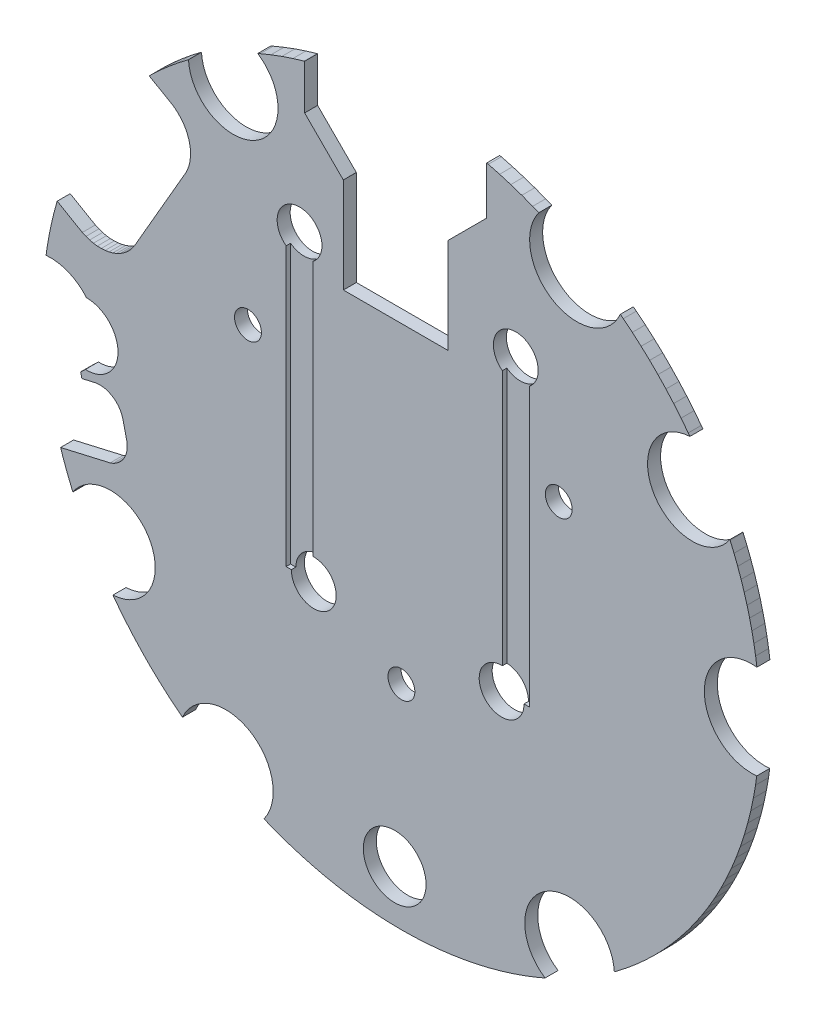
SolidWorks part; units mm, degrees
ref_plane "Płaszczyzna przednia" through (0, 0, 0) normal (0, 0, 1) x (1, 0, 0)
ref_plane "Płaszczyzna górna" through (0, 0, 0) normal (0, 1, 0) x (1, 0, 0)
ref_plane "Płaszczyzna prawa" through (0, 0, 0) normal (1, 0, 0) x (0, 0, -1)
sketch "Szkic1" plane through (0, 0, 0) normal (0, 0, 1) x (1, 0, 0)
  line L362 (-71.5796, -7.9834) -> (-71.3126, -9.14)
  line L363 (-71.3126, -9.14) -> (-68.5352, -8.4988)
  line L364 (-68.5352, -8.4988) -> (-68.1939, -8.42)
  line L365 (-68.1939, -8.42) -> (-67.4966, -8.3528)
  line L366 (-67.4966, -8.3528) -> (-66.7965, -8.3773)
  line L367 (-66.7965, -8.3773) -> (-66.1056, -8.4929)
  line L368 (-66.1056, -8.4929) -> (-65.4357, -8.6977)
  line L369 (-65.4357, -8.6977) -> (-64.7982, -8.9882)
  line L370 (-64.7982, -8.9882) -> (-64.2042, -9.3594)
  line L371 (-64.2042, -9.3594) -> (-63.6636, -9.805)
  line L372 (-63.6636, -9.805) -> (-63.1859, -10.3174)
  line L373 (-63.1859, -10.3174) -> (-62.7791, -10.8877)
  line L374 (-62.7791, -10.8877) -> (-62.4502, -11.5062)
  line L375 (-62.4502, -11.5062) -> (-62.2049, -12.1624)
  line L376 (-62.2049, -12.1624) -> (-62.1261, -12.5037)
  line L377 (-62.1261, -12.5037) -> (-61.3306, -15.949)
  line L378 (-61.3306, -15.949) -> (-61.2518, -16.2903)
  line L379 (-61.2518, -16.2903) -> (-61.1847, -16.9876)
  line L380 (-61.1847, -16.9876) -> (-61.2092, -17.6877)
  line L381 (-61.2092, -17.6877) -> (-61.3248, -18.3787)
  line L382 (-61.3248, -18.3787) -> (-61.5296, -19.0486)
  line L383 (-61.5296, -19.0486) -> (-61.8201, -19.686)
  line L384 (-61.8201, -19.686) -> (-62.1913, -20.2801)
  line L385 (-62.1913, -20.2801) -> (-62.6369, -20.8206)
  line L386 (-62.6369, -20.8206) -> (-63.1492, -21.2984)
  line L387 (-63.1492, -21.2984) -> (-63.7196, -21.7052)
  line L388 (-63.7196, -21.7052) -> (-64.3381, -22.0341)
  line L389 (-64.3381, -22.0341) -> (-64.9942, -22.2794)
  line L390 (-64.9942, -22.2794) -> (-65.3355, -22.3582)
  line L391 (-65.3355, -22.3582) -> (-76.0559, -24.8332)
  line L392 (-76.0559, -24.8332) -> (-75.5463, -26.3728)
  line L393 (-75.5463, -26.3728) -> (-74.6507, -28.8104)
  line L394 (-74.6507, -28.8104) -> (-73.6765, -31.2177)
  line L395 (-73.6765, -31.2177) -> (-73.3045, -32.0573)
  line L396 (-64.3703, -47.5137) -> (-63.5862, -48.5784)
  line L397 (-63.5862, -48.5784) -> (-61.8317, -50.7929)
  line L398 (-61.8317, -50.7929) -> (-60, -52.944)
  line L399 (-60, -52.944) -> (-58.0936, -55.0292)
  line L400 (-58.0936, -55.0292) -> (-56.1147, -57.0457)
  line L401 (-56.1147, -57.0457) -> (-54.0659, -58.9911)
  line L402 (-54.0659, -58.9911) -> (-51.9496, -60.863)
  line L403 (-51.9496, -60.863) -> (-49.7687, -62.659)
  line L404 (-49.7687, -62.659) -> (-48.854, -63.3595)
  line L405 (-30.6643, -73.9045) -> (-30.3309, -74.048)
  line L406 (-30.3309, -74.048) -> (-27.6979, -75.0726)
  line L407 (-27.6979, -75.0726) -> (-25.0304, -76.0036)
  line L408 (-25.0304, -76.0036) -> (-22.3317, -76.8399)
  line L409 (-22.3317, -76.8399) -> (-19.6051, -77.5804)
  line L410 (-19.6051, -77.5804) -> (-16.8541, -78.2241)
  line L411 (-16.8541, -78.2241) -> (-14.0821, -78.7703)
  line L412 (-14.0821, -78.7703) -> (-11.2926, -79.2184)
  line L413 (-11.2926, -79.2184) -> (-8.4889, -79.5676)
  line L414 (-8.4889, -79.5676) -> (-5.6747, -79.8177)
  line L415 (-5.6747, -79.8177) -> (-2.8534, -79.9683)
  line L416 (-2.8534, -79.9683) -> (-0.0286, -80.0192)
  line L417 (-0.0286, -80.0192) -> (2.7963, -79.9703)
  line L418 (2.7963, -79.9703) -> (5.6177, -79.8218)
  line L419 (5.6177, -79.8218) -> (8.4321, -79.5737)
  line L420 (8.4321, -79.5737) -> (11.236, -79.2264)
  line L421 (11.236, -79.2264) -> (14.0259, -78.7804)
  line L422 (14.0259, -78.7804) -> (16.7983, -78.2361)
  line L423 (16.7983, -78.2361) -> (19.5497, -77.5943)
  line L424 (19.5497, -77.5943) -> (22.2768, -76.8558)
  line L425 (22.2768, -76.8558) -> (24.9761, -76.0215)
  line L426 (24.9761, -76.0215) -> (27.6443, -75.0924)
  line L427 (27.6443, -75.0924) -> (30.278, -74.0697)
  line L428 (30.278, -74.0697) -> (32.0581, -73.3051)
  line L429 (47.514, -64.3751) -> (47.9923, -64.0295)
  line L430 (47.9923, -64.0295) -> (50.2037, -62.3107)
  line L431 (50.2037, -62.3107) -> (52.3536, -60.5156)
  line L432 (52.3536, -60.5156) -> (54.4394, -58.6463)
  line L433 (54.4394, -58.6463) -> (56.4584, -56.7052)
  line L434 (56.4584, -56.7052) -> (58.4083, -54.6947)
  line L435 (58.4083, -54.6947) -> (60.2867, -52.6171)
  line L436 (60.2867, -52.6171) -> (62.0911, -50.475)
  line L437 (62.0911, -50.475) -> (63.8195, -48.2711)
  line L438 (63.8195, -48.2711) -> (65.4698, -46.0081)
  line L439 (65.4698, -46.0081) -> (67.0398, -43.6887)
  line L440 (67.0398, -43.6887) -> (68.5277, -41.3158)
  line L441 (68.5277, -41.3158) -> (69.9316, -38.8923)
  line L442 (69.9316, -38.8923) -> (71.2498, -36.4211)
  line L443 (71.2498, -36.4211) -> (72.4808, -33.9053)
  line L444 (72.4808, -33.9053) -> (73.623, -31.348)
  line L445 (73.623, -31.348) -> (74.6749, -28.7523)
  line L446 (74.6749, -28.7523) -> (75.6354, -26.1213)
  line L447 (75.6354, -26.1213) -> (76.5032, -23.4583)
  line L448 (76.5032, -23.4583) -> (77.2773, -20.7666)
  line L449 (77.2773, -20.7666) -> (77.9567, -18.0495)
  line L450 (77.9567, -18.0495) -> (78.5407, -15.3102)
  line L451 (78.5407, -15.3102) -> (79.0284, -12.5522)
  line L452 (79.0284, -12.5522) -> (79.2994, -10.6289)
  line L453 (79.3336, 10.3964) -> (79.0449, 12.4201)
  line L454 (79.0449, 12.4201) -> (78.6613, 14.6547)
  line L455 (78.6613, 14.6547) -> (78.2145, 16.8775)
  line L456 (78.2145, 16.8775) -> (77.7049, 19.0868)
  line L457 (77.7049, 19.0868) -> (77.1329, 21.2808)
  line L458 (77.1329, 21.2808) -> (76.499, 23.4576)
  line L459 (76.499, 23.4576) -> (75.8037, 25.6157)
  line L460 (75.8037, 25.6157) -> (75.0475, 27.7531)
  line L461 (75.0475, 27.7531) -> (74.231, 29.8683)
  line L462 (74.231, 29.8683) -> (73.355, 31.9595)
  line L463 (73.355, 31.9595) -> (73.3082, 32.0629)
  line L464 (64.3736, 47.5139) -> (64.0078, 48.0184)
  line L465 (64.0078, 48.0184) -> (62.4143, 50.0722)
  line L466 (62.4143, 50.0722) -> (60.7549, 52.0732)
  line L467 (60.7549, 52.0732) -> (59.0313, 54.0192)
  line L468 (59.0313, 54.0192) -> (57.2455, 55.9082)
  line L469 (57.2455, 55.9082) -> (55.3992, 57.7382)
  line L470 (55.3992, 57.7382) -> (53.4945, 59.5072)
  line L471 (53.4945, 59.5072) -> (51.5333, 61.2135)
  line L472 (51.5333, 61.2135) -> (49.5177, 62.8551)
  line L473 (49.5177, 62.8551) -> (48.8544, 63.3604)
  line L474 (30.6602, 73.899) -> (29.2981, 74.4606)
  line L475 (29.2981, 74.4606) -> (26.864, 75.373)
  line L476 (26.864, 75.373) -> (24.4015, 76.2059)
  line L477 (24.4015, 76.2059) -> (21.9132, 76.9583)
  line L478 (21.9132, 76.9583) -> (19.4018, 77.6295)
  line L479 (19.4018, 77.6295) -> (19.0436, 77.7128)
  line L480 (19.0436, 77.7128) -> (19.0437, 67.0537)
  line L481 (19.0437, 67.0537) -> (10.4176, 58.4277)
  line L482 (10.4176, 58.4277) -> (10.4176, 37.1511)
  line L483 (10.4176, 37.1511) -> (-12.9504, 37.1511)
  line L484 (-12.9504, 37.1511) -> (-12.9504, 58.4177)
  line L485 (-12.9504, 58.4177) -> (-12.9604, 58.4177)
  line L486 (-12.9604, 58.4177) -> (-21.5964, 67.0537)
  line L487 (-21.5964, 67.0537) -> (-21.5964, 77.0457)
  line L488 (-21.5964, 77.0457) -> (-21.7211, 77.0127)
  line L489 (-21.7211, 77.0127) -> (-24.2112, 76.2665)
  line L490 (-24.2112, 76.2665) -> (-26.6758, 75.4398)
  line L491 (-26.6758, 75.4398) -> (-29.1122, 74.5335)
  line L492 (-29.1122, 74.5335) -> (-31.5179, 73.5485)
  line L493 (-31.5179, 73.5485) -> (-32.0595, 73.306)
  line L494 (-47.5141, 64.3762) -> (-47.8425, 64.1394)
  line L495 (-47.8425, 64.1394) -> (-49.8986, 62.5531)
  line L496 (-49.8986, 62.5531) -> (-51.9022, 60.9009)
  line L497 (-51.9022, 60.9009) -> (-53.8511, 59.1846)
  line L498 (-53.8511, 59.1846) -> (-55.7433, 57.406)
  line L499 (-55.7433, 57.406) -> (-56.2765, 56.8712)
  line L500 (-56.2765, 56.8712) -> (-51.5136, 54.1214)
  line L501 (-51.5136, 54.1214) -> (-51.1354, 53.903)
  line L502 (-51.1354, 53.903) -> (-50.4254, 53.3942)
  line L503 (-50.4254, 53.3942) -> (-49.7687, 52.8183)
  line L504 (-49.7687, 52.8183) -> (-49.1716, 52.1808)
  line L505 (-49.1716, 52.1808) -> (-48.6398, 51.4878)
  line L506 (-48.6398, 51.4878) -> (-48.1786, 50.746)
  line L507 (-48.1786, 50.746) -> (-47.7923, 49.9626)
  line L508 (-47.7923, 49.9626) -> (-47.4846, 49.1452)
  line L509 (-47.4846, 49.1452) -> (-47.2585, 48.3014)
  line L510 (-47.2585, 48.3014) -> (-47.1162, 47.4396)
  line L511 (-47.1162, 47.4396) -> (-47.0591, 46.568)
  line L512 (-47.0591, 46.568) -> (-47.0877, 45.695)
  line L513 (-47.0877, 45.695) -> (-47.2017, 44.829)
  line L514 (-47.2017, 44.829) -> (-47.4, 43.9784)
  line L515 (-47.4, 43.9784) -> (-47.6808, 43.1512)
  line L516 (-47.6808, 43.1512) -> (-48.0413, 42.3556)
  line L517 (-48.0413, 42.3556) -> (-48.2597, 41.9774)
  line L518 (-48.2597, 41.9774) -> (-59.4357, 22.62)
  line L519 (-59.4357, 22.62) -> (-59.654, 22.2418)
  line L520 (-59.654, 22.2418) -> (-60.1628, 21.5318)
  line L521 (-60.1628, 21.5318) -> (-60.7387, 20.8751)
  line L522 (-60.7387, 20.8751) -> (-61.3762, 20.278)
  line L523 (-61.3762, 20.278) -> (-62.0692, 19.7462)
  line L524 (-62.0692, 19.7462) -> (-62.811, 19.285)
  line L525 (-62.811, 19.285) -> (-63.5944, 18.8986)
  line L526 (-63.5944, 18.8986) -> (-64.4119, 18.591)
  line L527 (-64.4119, 18.591) -> (-65.2556, 18.3649)
  line L528 (-65.2556, 18.3649) -> (-66.1174, 18.2226)
  line L529 (-66.1174, 18.2226) -> (-66.989, 18.1655)
  line L530 (-66.989, 18.1655) -> (-67.862, 18.1941)
  line L531 (-67.862, 18.1941) -> (-68.728, 18.3081)
  line L532 (-68.728, 18.3081) -> (-69.5787, 18.5064)
  line L533 (-69.5787, 18.5064) -> (-70.4058, 18.7872)
  line L534 (-70.4058, 18.7872) -> (-71.2014, 19.1477)
  line L535 (-71.2014, 19.1477) -> (-71.5796, 19.366)
  line L536 (-71.5796, 19.366) -> (-76.8174, 22.3901)
  line L537 (-76.8174, 22.3901) -> (-76.8834, 22.1744)
  line L538 (-76.8834, 22.1744) -> (-77.5625, 19.6678)
  line L539 (-77.5625, 19.6678) -> (-78.1599, 17.1405)
  line L540 (-78.1599, 17.1405) -> (-78.6749, 14.5952)
  line L541 (-78.6749, 14.5952) -> (-79.1071, 12.0345)
  line L542 (-79.1071, 12.0345) -> (-79.2897, 10.6872)
  circle A3 centre (0, -32.54) radius 3
  circle A4 centre (35.1087, 20.27) radius 3
  circle A5 centre (-34.2427, 19.77) radius 3
  arc A16 (-71.5796, -7.9834) -> (-79.2897, 10.6872) centre (-78.3301, 0.1563) ccw
  arc A17 (-64.3703, -47.5137) -> (-73.3045, -32.0573) centre (-64.9348, -37.5297) ccw
  arc A18 (-30.6643, -73.9045) -> (-48.854, -63.3595) centre (-39.186, -67.6433) ccw
  arc A19 (47.514, -64.3751) -> (32.0581, -73.3051) centre (37.5297, -64.9348) ccw
  arc A20 (79.3336, 10.3964) -> (79.2994, -10.6289) centre (78.1738, -0.1144) ccw
  arc A21 (64.3736, 47.5139) -> (73.3082, 32.0629) centre (64.9348, 37.5297) ccw
  arc A22 (30.6602, 73.899) -> (48.8544, 63.3604) centre (39.186, 67.6433) ccw
  arc A23 (-47.5141, 64.3762) -> (-32.0595, 73.306) centre (-37.5297, 64.9348) ccw
extrude "Dodanie-wyciągnięcie1" add sketch "Szkic1" along normal blind 2.9
sketch "Sketch1" plane through (0, 0, 2.9) normal (0, 0, 1) x (1, 0, 0)
  line L6 (22.531, 39.311) -> (22.531, -17.7321)
  line L7 (28.531, 39.311) -> (28.531, -22.689)
  line L8 (28.531, -22.689) -> (27.3558, -22.689)
  line L9 (-19.729, 39.311) -> (-19.729, -17.7321)
  line L10 (-25.729, 39.311) -> (-25.729, -22.689)
  line L11 (-25.729, -22.689) -> (-24.5539, -22.6966)
  arc A4 (22.531, -17.7321) -> (27.3558, -22.689) centre (22.356, -22.729) ccw
  arc A5 (-24.5539, -22.6966) -> (-19.729, -17.7321) centre (-19.554, -22.729) ccw
  arc A6 (28.531, 39.311) -> (22.531, 39.311) centre (25.531, 43.311) ccw
  arc A7 (-19.729, 39.311) -> (-25.729, 39.311) centre (-22.729, 43.311) ccw
  point P0 (0, 0)
extrude "Cut-Extrude1" cut sketch "Sketch1" against normal blind 1 contours A7 L10 L11 A5 L9 | A6 L6 A4 L8 L7
sketch "Sketch2" plane through (0, 0, 2.9) normal (0, 0, 1) x (1, 0, 0)
  circle A0 centre (-22.729, 43.311) radius 5
  circle A1 centre (25.531, 43.311) radius 5
  circle A2 centre (22.356, -22.729) radius 5
  circle A3 centre (-19.554, -22.729) radius 5
extrude "Cut-Extrude2" cut sketch "Sketch2" against normal through all
sketch "Sketch3" plane through (0, 0, 2.9) normal (0, 0, 1) x (1, 0, 0)
  line L0 (0, 0) -> (0, -68.54) construction
  line L1 (0, -68.54) -> (-1.5, -68.54) construction
  line L2 (0, 0) -> (-76.8972, 0) construction
  circle A0 centre (0, -32.54) radius 3 construction
  circle A1 centre (-1.5, -68.54) radius 7
  circle A2 centre (-34.2427, 19.77) radius 3 construction
  circle A3 centre (-70.2427, 0) radius 7
  point P7 (-3, -32.54)
  point P8 (72.1497, -57.8392)
  point P10 (3, -32.54)
  dimension "D2" = 14
  dimension "D3" = 4.5
  dimension "D4" = 14
  dimension "D1" = 36
  dimension "D5" = 36
extrude "Cut-Extrude3" cut sketch "Sketch3" against normal through all
